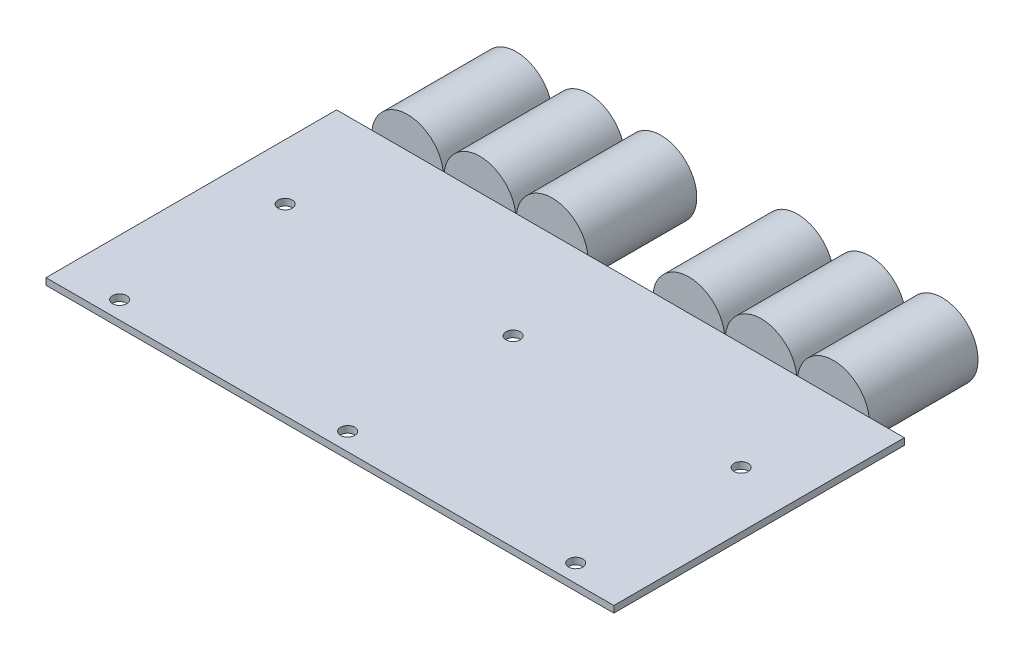
SolidWorks part; units mm, degrees
ref_plane "Front Plane" through (0, 0, 0) normal (0, 0, 1) x (1, 0, 0)
ref_plane "Top Plane" through (0, 0, 0) normal (0, 1, 0) x (1, 0, 0)
ref_plane "Right Plane" through (0, 0, 0) normal (1, 0, 0) x (0, 0, -1)
sketch "Sketch1" plane through (0, 0, 0) normal (0, 1, 0) x (1, 0, 0)
  line L1 (64, 32.75) -> (-64, 32.75)
  line L2 (64, 32.75) -> (64, -32.75)
  line L3 (64, -32.75) -> (-64, -32.75)
  line L4 (-64, 32.75) -> (-64, -32.75)
  line L5 (64, 32.75) -> (-64, -32.75) construction
  line L6 (64, -32.75) -> (-64, 32.75) construction
  point P0 (0, 0)
  dimension "D1" = 65.5
  dimension "D2" = 128
extrude "Boss-Extrude1" add sketch "Sketch1" along normal blind 1.5
sketch "Sketch2" plane through (0, 0, 0) normal (0, 1, 0) x (1, 0, 0)
  line L0 (0, 8.55) -> (0, -28.75) construction
  line L2 (-64, -32.75) -> (64, -32.75) construction
  line L3 (-64, 32.75) -> (-64, -32.75) construction
  circle A0 centre (-51.4, -28.75) radius 1.6
  circle A1 centre (0, -28.75) radius 1.6
  circle A2 centre (51.4, -28.75) radius 1.6
  circle A3 centre (-51.4, 8.55) radius 1.6
  circle A4 centre (0, 8.55) radius 1.6
  circle A5 centre (51.4, 8.55) radius 1.6
  dimension "D1" = 3.2
  dimension "D2" = 2.4
  dimension "D4" = 48.2
  dimension "D5" = 34.1
  dimension "D3" = 11
extrude "Cut-Extrude2" cut sketch "Sketch2" along normal through all
sketch "Sketch3" plane through (0, 0, 0) normal (0, -1, 0) x (1, 0, 0)
  line L0 (-64, 32.75) -> (64, 32.75) construction
  line L1 (52.5, 1.75) -> (-52.5, 1.75)
  line L2 (52.5, 1.75) -> (52.5, 19.75)
  line L3 (52.5, 19.75) -> (-52.5, 19.75)
  line L4 (-52.5, 1.75) -> (-52.5, 19.75)
  line L5 (52.5, 1.75) -> (-52.5, 19.75) construction
  line L6 (52.5, 19.75) -> (-52.5, 1.75) construction
  point P0 (0, 10.75)
  dimension "D1" = 105
  dimension "D2" = 18
  dimension "D3" = 13
extrude "Boss-Extrude2" add sketch "Sketch3" along normal blind 1
sketch "Sketch4" plane through (0, 0, -32.75) normal (0, 0, -1) x (-1, 0, 0)
  line L0 (0, 0) -> (0, 1.5) construction
  line L1 (-64, 1.5) -> (64, 1.5) construction
  circle A0 centre (-48, 0.5) radius 8.1
  circle A1 centre (-31.7, 0.5) radius 8.1
  circle A2 centre (-15.4, 0.5) radius 8.1
  circle A3 centre (15.4, 0.5) radius 8.1
  circle A4 centre (31.7, 0.5) radius 8.1
  circle A5 centre (48, 0.5) radius 8.1
  dimension "D1" = 16.2
  dimension "D2" = 1
  dimension "D3" = 48
  dimension "D4" = 16.3
  dimension "D5" = 16.3
extrude "Boss-Extrude4" add sketch "Sketch4" along normal offset from surface (24.5 mm away) 90 up to face at (0, 0.75, 32.75)
sketch "Sketch5" plane through (0, 0, 0) normal (0, -1, 0) x (1, 0, 0)
  line L0 (0, 0) -> (0, -32.75) construction
  line L1 (-60.8295, 25.8925) -> (-58.9862, 25.8925)
  line L2 (-60.8295, 25.8925) -> (-60.8295, 12.4221)
  line L3 (-60.8295, 12.4221) -> (-58.9862, 12.4221)
  line L4 (-58.9862, 25.8925) -> (-58.9862, 12.4221)
  line L5 (-62.8146, 10.8624) -> (-60.8295, 10.8624)
  line L6 (-62.8146, 10.8624) -> (-62.8146, -6.4365)
  line L7 (-62.8146, -6.4365) -> (-60.8295, -6.4365)
  line L8 (-60.8295, 10.8624) -> (-60.8295, -6.4365)
  line L9 (-44.25, -6.15) -> (-3.25, -6.15)
  line L10 (-44.25, -6.15) -> (-44.25, -23.15)
  line L11 (-44.25, -23.15) -> (-3.25, -23.15)
  line L12 (-3.25, -6.15) -> (-3.25, -23.15)
  line L17 (7.3154, -32.75) -> (-7.3154, -32.75) construction
  line L18 (3.25, -6.15) -> (3.25, -23.15)
  line L19 (44.25, -23.15) -> (3.25, -23.15)
  line L20 (44.25, -6.15) -> (44.25, -23.15)
  line L21 (44.25, -6.15) -> (3.25, -6.15)
  line L22 (60.8295, 10.8624) -> (60.8295, -6.4365)
  line L23 (62.8146, -6.4365) -> (60.8295, -6.4365)
  line L24 (62.8146, 10.8624) -> (62.8146, -6.4365)
  line L25 (62.8146, 10.8624) -> (60.8295, 10.8624)
  line L26 (58.9862, 25.8925) -> (58.9862, 12.4221)
  line L27 (60.8295, 12.4221) -> (58.9862, 12.4221)
  line L28 (60.8295, 25.8925) -> (60.8295, 12.4221)
  line L29 (60.8295, 25.8925) -> (58.9862, 25.8925)
  line L30 (-64, -30.15) -> (64, -30.15)
  line L31 (-64, -32.75) -> (-64, 32.75) construction
  line L32 (64, 32.75) -> (64, -32.75) construction
  line L34 (-44.25, -23.15) -> (-30.25, -23.15)
  line L35 (-44.25, -23.15) -> (-44.25, -26.65)
  line L36 (-44.25, -26.65) -> (-30.25, -26.65)
  line L37 (-30.25, -23.15) -> (-30.25, -26.65)
  line L38 (3.25, -23.15) -> (17.25, -23.15)
  line L39 (3.25, -23.15) -> (3.25, -26.65)
  line L40 (3.25, -26.65) -> (17.25, -26.65)
  line L41 (17.25, -23.15) -> (17.25, -26.65)
  line L42 (54.4533, 8.528) -> (57.4966, 8.528)
  line L43 (54.4533, 8.528) -> (54.4533, -0.6019)
  line L44 (54.4533, -0.6019) -> (57.4966, -0.6019)
  line L45 (57.4966, 8.528) -> (57.4966, -0.6019)
  dimension "D1" = 9.6
  dimension "D2" = 41
  dimension "D3" = 6.5
  dimension "D4" = 17
  dimension "D5" = 7
  dimension "D6" = 14
  dimension "D7" = 3.5
sketch "Sketch6" plane through (0, 0, 0) normal (0, -1, 0) x (1, 0, 0)
  line L0 (-42, 32.75) -> (-42, 52.75) construction
  line L1 (-64, 32.75) -> (64, 32.75)
  line L2 (-64, 32.75) -> (-64, 52.75)
  line L3 (-64, 52.75) -> (64, 52.75)
  line L4 (64, 32.75) -> (64, 52.75)
  line L5 (-26, 32.75) -> (-26, 52.75) construction
  line L6 (-10, 52.75) -> (-10, 32.75) construction
  line L7 (0, 52.75) -> (0, 32.75) construction
  line L8 (10, 52.75) -> (10, 32.75) construction
  line L9 (26, 32.75) -> (26, 52.75) construction
  line L10 (42, 32.75) -> (42, 52.75) construction
  dimension "D1" = 20
  dimension "D2" = 22
  dimension "D3" = 16
  dimension "D4" = 16
equation "\"D4@Sketch4\"=\"D1@Sketch4\"+.1"
equation "\"D5@Sketch4\"=\"D4@Sketch4\""
